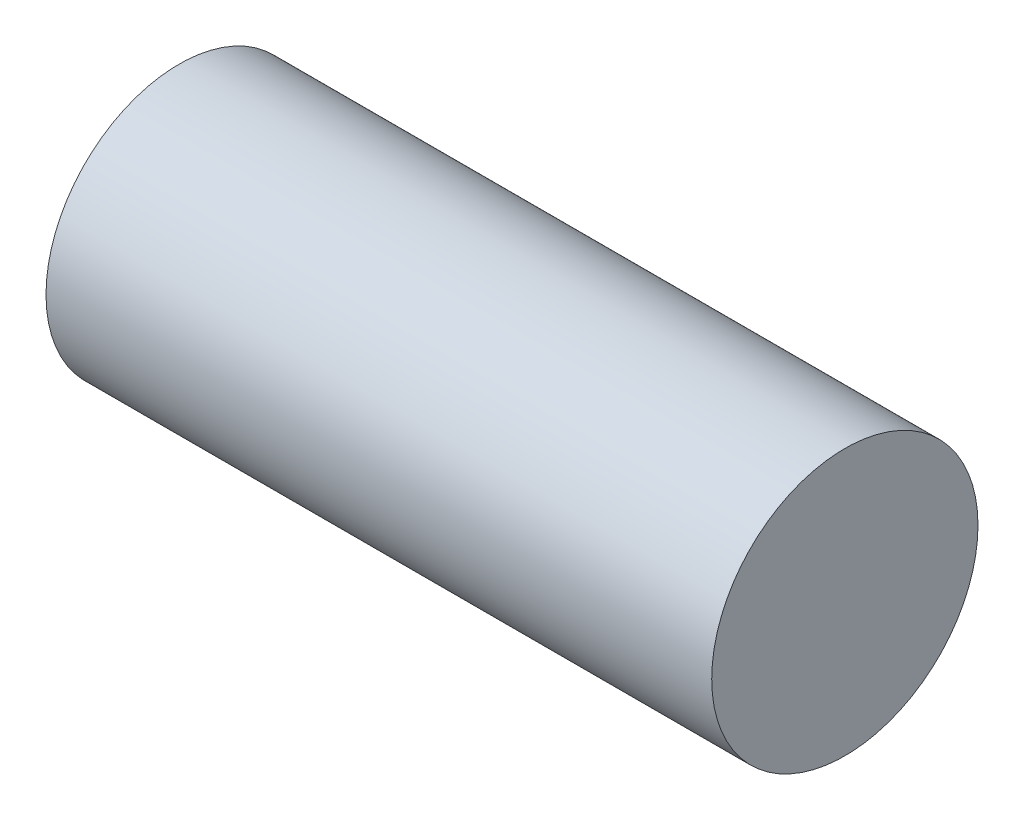
SolidWorks part; units mm, degrees
ref_plane "Front Plane" through (0, 0, 0) normal (0, 0, 1) x (1, 0, 0)
ref_plane "Top Plane" through (0, 0, 0) normal (0, 1, 0) x (1, 0, 0)
ref_plane "Right Plane" through (0, 0, 0) normal (1, 0, 0) x (0, 0, -1)
sketch "Axial blank profile" plane through (0, 0, 0) normal (0, 0, 1) x (1, 0, 0)
  line L0 (-60, 0) -> (30, 0) construction
  line L1 (-17, 0) -> (3, 0)
  line L2 (3, 0) -> (3, 4)
  line L3 (3, 4) -> (-17, 4)
  line L4 (-17, 4) -> (-17, 0)
revolve "Native revolved blank" add sketch "Axial blank profile" angle 360 about L0
